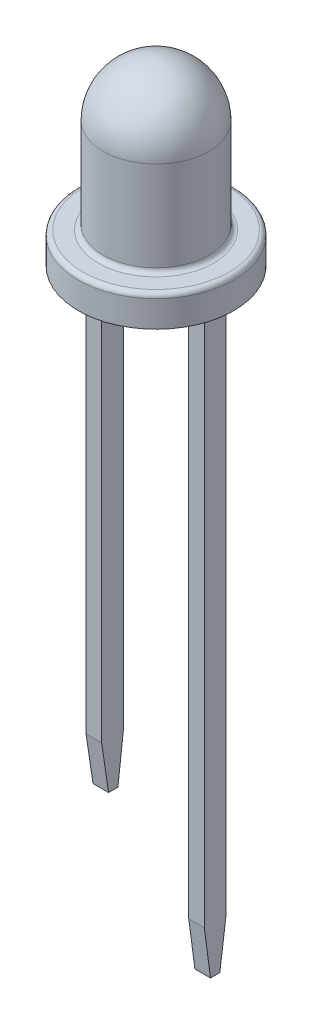
SolidWorks part; units mm, degrees
ref_plane "Front Plane" through (0, 0, 0) normal (0, 0, 1) x (1, 0, 0)
ref_plane "Top Plane" through (0, 0, 0) normal (0, 1, 0) x (1, 0, 0)
ref_plane "Right Plane" through (0, 0, 0) normal (1, 0, 0) x (0, 0, -1)
sketch "Sketch1" plane through (0, 0, 0) normal (0, 0, 1) x (1, 0, 0)
  line L0 (0, 0) -> (0, 19.4)
  line L1 (-0.1, 19.5) -> (-0.4, 19.5)
  line L2 (-0.5, 19.6) -> (-0.5, 20.5)
  line L4 (-1, 20.5) -> (-2, 19.5)
  line L5 (-2, 19.5) -> (-1.1, 19.5)
  line L6 (-1, 19.4) -> (-1, 19.1)
  line L7 (-0.9, 19) -> (-0.6, 19)
  line L8 (-0.5, 18.9) -> (-0.5, 0)
  line L9 (-0.5, 0) -> (0, 0)
  line L10 (-1, 20.5) -> (-1, 21)
  line L11 (-1, 21) -> (-0.5, 21)
  line L12 (-0.5, 21) -> (-0.5, 20.5)
  arc A0 (-1, 19.1) -> (-0.9, 19) centre (-0.9, 19.1) ccw
  arc A1 (-0.6, 19) -> (-0.5, 18.9) centre (-0.6, 18.9) cw
  arc A2 (0, 19.4) -> (-0.1, 19.5) centre (-0.1, 19.4) ccw
  arc A3 (-0.4, 19.5) -> (-0.5, 19.6) centre (-0.4, 19.6) cw
  arc A4 (-1.1, 19.5) -> (-1, 19.4) centre (-1.1, 19.4) cw
  point P11 (0, 0)
  point P13 (-0.25, 19.5)
  point P17 (-1, 19)
  point P20 (-0.5, 19)
  point P23 (0, 19.5)
  point P26 (-0.5, 19.5)
  point P29 (-1, 19.5)
  dimension "D7" = 0.1
  dimension "D1" = 0.5
  dimension "D2" = 1.5
  dimension "D3" = 0.5
  dimension "D4" = 0.5
  dimension "D5" = 0.5
  dimension "D6" = 0.5
  dimension "D8" = 19
  dimension "D9" = 0.5
  dimension "D10" = 0.5
extrude "Boss-Extrude1" add sketch "Sketch1" along normal mid plane 0.7
sketch "Sketch2" plane through (0, 0, 0) normal (0, 0, 1) x (1, 0, 0)
  line L0 (-2.2707, 19.5293) -> (-1.3293, 20.4707)
  line L1 (-1.3, 20.5414) -> (-1.3, 21)
  line L2 (-1.3, 21) -> (-3.3, 21)
  line L3 (-3.3, 21) -> (-3.3, 19.6)
  line L4 (-3.4, 19.5) -> (-3.7, 19.5)
  line L5 (-2.3414, 19.5) -> (-2.7, 19.5)
  line L6 (-2.8, 19.4) -> (-2.8, 19.0173)
  line L7 (-2.9, 18.9173) -> (-3.2, 18.9173)
  line L8 (-3.3, 18.8173) -> (-3.3, 3.5)
  line L9 (-3.3, 3.5) -> (-3.8, 3.5)
  line L10 (-3.8, 3.5) -> (-3.8, 19.4)
  line L11 (-1, 21) -> (-1, 20.5) construction
  line L12 (-2, 19.5) -> (-1.1, 19.5) construction
  line L13 (-0.5, 18.9) -> (-0.5, 0) construction
  line L14 (-0.5, 21) -> (-1, 21) construction
  arc A0 (-3.2, 18.9173) -> (-3.3, 18.8173) centre (-3.2, 18.8173) ccw
  arc A1 (-2.8, 19.0173) -> (-2.9, 18.9173) centre (-2.9, 19.0173) cw
  arc A2 (-1.3293, 20.4707) -> (-1.3, 20.5414) centre (-1.4, 20.5414) ccw
  arc A3 (-2.2707, 19.5293) -> (-2.3414, 19.5) centre (-2.3414, 19.6) cw
  arc A4 (-2.7, 19.5) -> (-2.8, 19.4) centre (-2.7, 19.4) ccw
  arc A5 (-3.7, 19.5) -> (-3.8, 19.4) centre (-3.7, 19.4) ccw
  arc A6 (-3.3, 19.6) -> (-3.4, 19.5) centre (-3.4, 19.6) cw
  point P23 (-3.3, 18.9173)
  point P26 (-2.8, 18.9173)
  point P29 (-1.3, 20.5)
  point P32 (-2.3, 19.5)
  point P35 (-2.8, 19.5)
  point P38 (-3.8, 19.5)
  point P41 (-3.3, 19.5)
  dimension "D11" = 0.1
  dimension "D1" = 0.3
  dimension "D2" = 2
  dimension "D3" = 0.5
  dimension "D4" = 0.5
  dimension "D5" = 0.5
  dimension "D6" = 0.5
  dimension "D7" = 0.5
  dimension "D8" = 16
  dimension "D9" = 2.8
  dimension "D10" = 0.3
extrude "Boss-Extrude2" add sketch "Sketch2" along normal mid plane 0.7 separate body
sketch "Sketch3" plane through (0, 0, 0) normal (0, 0, 1) x (1, 0, 0)
  line L0 (-1.3, 20.8544) -> (-1, 20.8544) construction
  line L1 (-1.1872, 20.8544) -> (-1.1872, 21.1604) construction
  line L2 (-1.1872, 20.8544) -> (-1.1872, 21.1604)
  line L3 (-1.1872, 21.1604) -> (-0.6872, 21.0371)
  line L4 (-1.3, 20.5414) -> (-1.3, 21) construction
  line L5 (-1, 21) -> (-1, 20.5) construction
  arc A0 (-0.6872, 21.0371) -> (-1.1872, 20.8544) centre (-1.1794, 21.6084) cw
  dimension "D1" = 0.5
revolve "Cut-Revolve2" cut sketch "Sketch3" angle 360 about L2
sketch "Sketch5" plane through (0, 0, 0) normal (0, 0, 1) x (1, 0, 0)
  line L2 (-1.1872, 21.1604) -> (-1.1872, 20.8544)
  line L3 (-0.6872, 21.0371) -> (-1.1872, 21.1604)
  line L4 (-1.1872, 20.9679) -> (-1.1872, 20.8544)
  arc A1 (-1.1872, 20.8544) -> (-0.6872, 21.0371) centre (-1.1794, 21.6084) ccw
  arc A2 (-1.1872, 20.8544) -> (-0.6872, 21.0371) centre (-1.1794, 21.6084) ccw
  spline S0 degree 3 poles (-1.1872, 20.9679) (-1.019, 20.9691) (-0.8557, 21.0182) (-0.6872, 21.0371) knots 0 0 0 0 1 1 1 1
  dimension "D1" = 0
revolve "Revolve2" add sketch "Sketch5" angle 360 about L4
sketch "Sketch7" plane through (0, 0, 0) normal (0, 0, 1) x (1, 0, 0)
  line L0 (-3.8, 18.8) -> (0, 18.8) construction
  line L1 (-3.8, 19.4) -> (-3.8, 3.5) construction
  line L2 (0, 0) -> (0, 19.4) construction
  line L3 (-1.9, 18.8) -> (-1.9, 24.5331) construction
  line L4 (-0.1951, 22.838) -> (-0.1951, 19.95)
  line L5 (-0.0451, 19.8) -> (0.45, 19.8)
  line L6 (0.6, 19.65) -> (0.6, 18.8)
  line L7 (0.6, 18.8) -> (-1.9, 18.8)
  line L8 (-0.9, 19) -> (-0.6, 19) construction
  line L9 (-1.9, 18.8) -> (-1.9, 24.5331)
  arc A0 (-1.9, 24.5331) -> (-0.1951, 22.838) centre (-1.8951, 22.8331) cw
  arc A1 (0.45, 19.8) -> (0.6, 19.65) centre (0.45, 19.65) cw
  arc A2 (-0.1951, 19.95) -> (-0.0451, 19.8) centre (-0.0451, 19.95) ccw
  point P15 (-0.75, 19)
  point P20 (-0.1951, 19.8)
  dimension "D1" = 1.7
  dimension "D5" = 0.15
  dimension "D2" = 1
  dimension "D3" = 0.2
  dimension "D4" = 3.038
  dimension "D6" = 2.5
revolve "Revolve6" add sketch "Sketch7" angle 360 about L9
sketch "Sketch8" plane through (0, 0, 0) normal (1, 0, 0) x (0, 0, -1)
  line L0 (-0.35, 1.5) -> (0.35, 1.5) construction
  line L1 (-0.35, 0) -> (-0.35, 19.4) construction
  line L2 (0.35, 0) -> (0.35, 19.4) construction
  line L3 (-0.35, 0) -> (0.35, 0) construction
  line L4 (-0.15, 0) -> (0.15, 0)
  line L5 (0.15, 0) -> (0.35, 1.5)
  line L6 (0.35, 1.5) -> (0.35, 0)
  line L7 (0.35, 0) -> (-0.35, 0)
  line L8 (-0.35, 0) -> (-0.35, 1.5)
  line L9 (-0.35, 1.5) -> (-0.15, 0)
  point P12 (0, 0)
  line M2 (0.35, 0) -> (0.35, 19.4)
  line M4 (-0.35, 19.4) -> (-0.35, 0)
  line M5 (-0.35, 0) -> (0.35, 0)
  dimension "D1" = 1.5
  dimension "D2" = 0.3
extrude "Cut-Extrude1" cut sketch "Sketch8" against normal blind 0.7 contours L5 M5 M2 | L9 M4 M5
sketch "Sketch9" plane through (-3.8, 0, 0) normal (-1, 0, 0) x (0, 0, 1)
  line L0 (-0.35, 5) -> (0.35, 5) construction
  line L1 (-0.35, 19.4) -> (-0.35, 3.5) construction
  line L2 (0.35, 19.4) -> (0.35, 3.5) construction
  line L3 (0.35, 3.5) -> (-0.35, 3.5) construction
  line L4 (-0.1739, 3.5) -> (0.1261, 3.5)
  line L5 (0.1261, 3.5) -> (0.35, 5)
  line L6 (0.35, 5) -> (0.35, 3.5)
  line L7 (0.35, 3.5) -> (-0.35, 3.5)
  line L8 (-0.35, 3.5) -> (-0.35, 5)
  line L9 (-0.35, 5) -> (-0.1739, 3.5)
  point P8 (0, 0)
  point P11 (-0.0239, 3.5)
  line M2 (-0.35, 19.4) -> (-0.35, 3.5)
  line M3 (-0.35, 3.5) -> (0.35, 3.5)
  line M4 (0.35, 3.5) -> (0.35, 19.4)
  dimension "D1" = 1.5
  dimension "D2" = 0.3
extrude "Cut-Extrude2" cut sketch "Sketch9" against normal blind 0.7 contours L9 M2 M3 | L5 M3 M4
